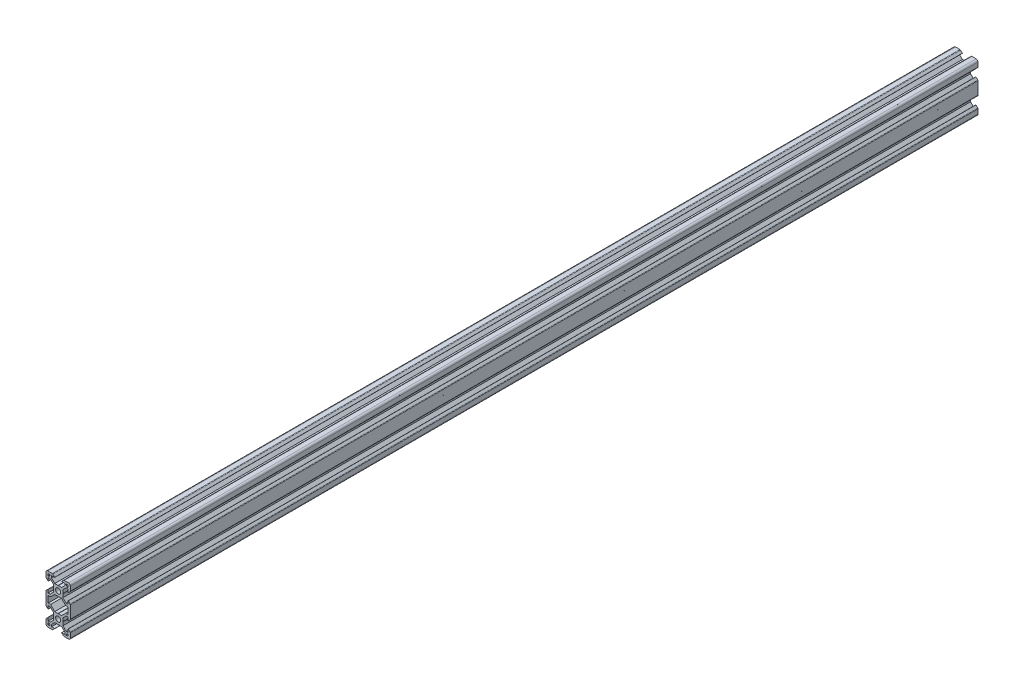
SolidWorks part; units mm, degrees
ref_plane "Front Plane" through (0, 0, 0) normal (0, 0, 1) x (1, 0, 0)
ref_plane "Top Plane" through (0, 0, 0) normal (0, 1, 0) x (1, 0, 0)
ref_plane "Right Plane" through (0, 0, 0) normal (1, 0, 0) x (0, 0, -1)
sketch "Sketch1" plane through (0, 0, 0) normal (0, 0, 1) x (1, 0, 0)
  line L0 (-8.2, 2.8875) -> (-8.2, 5.4975)
  line L3 (-4.9072, 9.9975) -> (-8.5, 9.9975)
  line L4 (-10, 4.9047) -> (-10, 8.4975)
  line L5 (-2.1, 0) -> (-3.8, 0) construction
  line L6 (0, 3.8) -> (0, 0) construction
  line L7 (-0.1, 3.9) -> (-2.8404, 3.9)
  line L8 (-3.9, 0.1) -> (-3.9, 2.8383)
  line L9 (-2.89, 8.1975) -> (-5.5, 8.1975)
  line L10 (-6.57, 8.1975) -> (-6.57, 7.6575)
  line L11 (-8.2, 6.5675) -> (-7.66, 6.5675)
  line L12 (-5.5, 8.1975) -> (-5.5, 6.5588)
  line L13 (-6.56, 5.4975) -> (-8.2, 5.4975)
  line L14 (-8.2, 8.1975) -> (-1.4852, 1.4847) construction
  line L15 (-6.56, 5.4975) -> (-3.9, 2.8383)
  line L16 (-5.5, 6.5588) -> (-2.8404, 3.9)
  line L17 (-7.66, 6.5675) -> (-6.57, 7.6575)
  line L18 (-8.7302, 7.6671) -> (-0.5302, -0.5304) construction
  line L19 (-7.6698, 8.7279) -> (0.5302, 0.5304) construction
  line L20 (-8.2, 8.1975) -> (0, 0) construction
  line L21 (-8.2, 6.5675) -> (-8.2, 8.1975)
  line L22 (-8.2, -0.0025) -> (-8.2, 8.1975) construction
  line L23 (-6.57, 8.1975) -> (-8.2, 8.1975)
  line L24 (0, 8.1975) -> (-8.2, 8.1975) construction
  line L25 (-10, -0.0025) -> (-10, 9.9975) construction
  line L26 (0, 9.9975) -> (-10, 9.9975) construction
  line L27 (-2.89, 8.3075) -> (-2.89, 8.1975)
  line L29 (-8.31, 2.8875) -> (-8.2, 2.8875)
  line L30 (-4.3486, 9.7661) -> (-2.89, 8.3075)
  line L31 (-8.31, 2.8875) -> (-9.7686, 4.3461)
  line L34 (-0.1, 3.9) -> (0, 3.8)
  line L35 (-3.9, 0.1) -> (-3.8, 0)
  line L36 (-8.2, -7.2996) -> (-6.24, -7.2996)
  line L37 (0, 0) -> (0, -10) construction
  line L38 (-0.1, -3.9) -> (-2.8404, -3.9)
  line L39 (-3.8, 0) -> (-3.9, -0.1)
  line L40 (-3.9, -0.1) -> (-3.9, -2.84)
  line L41 (-2.8404, -3.9) -> (-6.24, -7.2996)
  line L42 (-3.9, -2.84) -> (-6.56, -5.5)
  line L43 (-8.2, -2.89) -> (-8.2, -5.5)
  line L44 (-6.56, 5.4975) -> (-6.56, -5.5) construction
  line L45 (-6.56, -5.5) -> (-8.2, -5.5)
  line L46 (-0.1, -3.9) -> (0, -3.8)
  line L48 (-8.2, -2.89) -> (-8.31, -2.89)
  line L49 (-8.31, -2.89) -> (-9.7657, -4.3457)
  line L52 (-10, -10) -> (0, -10) construction
  line L53 (-8.2, -7.2996) -> (-8.2, -10)
  line L61 (-10, -4.9114) -> (-10, -10)
  arc A1 (-10, 8.4975) -> (-8.5, 9.9975) centre (-8.5, 8.4975) cw
  arc A2 (-9.7686, 4.3461) -> (-10, 4.9047) centre (-9.21, 4.9047) cw
  arc A3 (-4.3486, 9.7661) -> (-4.9072, 9.9975) centre (-4.9072, 9.2075) ccw
  arc A4 (-9.7657, -4.3457) -> (-10, -4.9114) centre (-9.2, -4.9114) ccw
  arc A6 (0, 2.1) -> (0, -2.1) centre (0, 0) ccw
  point P29 (-10, 9.9975)
  point P39 (-10, 4.5775)
  point P42 (-4.58, 9.9975)
  point P48 (-10, -4.58)
  dimension "D15" = 1.5
  dimension "D22" = 0.79
  dimension "D30" = 1.96
  dimension "D31" = 2.1
  dimension "D39" = 0.8
  dimension "D4" = 1.8
  dimension "D5" = 3.43
  dimension "D6" = 3.43
  dimension "D7" = 0.54
  dimension "D8" = 0.54
  dimension "D9" = 1.07
  dimension "D10" = 1.07
  dimension "D11" = 3.9
  dimension "D12" = 3.9
  dimension "D16" = 7.11
  dimension "D17" = 0.11
  dimension "D18" = 1.69
  dimension "D19" = 0.11
  dimension "D20" = 7.11
  dimension "D21" = 1.69
  dimension "D23" = 10
  dimension "D24" = 0.1
  dimension "D25" = 45
  dimension "D26" = 0.1
  dimension "D27" = 45
  dimension "D28" = 1.64
  dimension "D29" = 10
  dimension "D32" = 3.9
  dimension "D33" = 45
  dimension "D34" = 2.74
  dimension "D35" = 45
  dimension "D37" = 2.61
  dimension "D38" = 90
  dimension "D40" = 0.1
  dimension "D41" = 45
  dimension "D13" = 0.75
  dimension "D14" = 0.75
sketch "Sketch2" plane through (0, 0, 0) normal (0, 0, 1) x (1, 0, 0)
  line L0 (-0.1, 3.9) -> (0, 3.8) construction
  line L1 (-0.1, 3.9) -> (-2.8404, 3.9) construction
  line L2 (-5.5, 6.5588) -> (-2.8404, 3.9) construction
  line L3 (-5.5, 8.1975) -> (-5.5, 6.5588) construction
  line L4 (-2.89, 8.1975) -> (-5.5, 8.1975) construction
  line L5 (-7.66, 6.5675) -> (-6.57, 7.6575)
  line L6 (-6.57, 7.6575) -> (-6.57, 8.1975)
  line L7 (-6.57, 8.1975) -> (-8.2, 8.1975)
  line L8 (-8.2, 8.1975) -> (-8.2, 6.5675)
  line L9 (-8.2, 6.5675) -> (-7.66, 6.5675)
  line L10 (-7.66, 6.5675) -> (-6.57, 7.6575)
  line L11 (-6.57, 7.6575) -> (-6.57, 8.1975)
  line L12 (-6.57, 8.1975) -> (-8.2, 8.1975)
  line L13 (-8.2, 8.1975) -> (-8.2, 6.5675)
  line L14 (-8.2, 6.5675) -> (-7.66, 6.5675)
  line L15 (-2.89, 8.3075) -> (-2.89, 8.1975) construction
  line L16 (-4.3486, 9.7661) -> (-2.89, 8.3075) construction
  line L17 (-4.9072, 9.9975) -> (-8.5, 9.9975) construction
  line L18 (-10, 4.9047) -> (-10, 8.4975) construction
  line L19 (-8.31, 2.8875) -> (-9.7686, 4.3461) construction
  line L20 (-8.31, 2.8875) -> (-8.2, 2.8875) construction
  line L21 (-8.2, 2.8875) -> (-8.2, 5.4975) construction
  line L22 (-6.56, 5.4975) -> (-8.2, 5.4975) construction
  line L23 (-6.56, 5.4975) -> (-3.9, 2.8383) construction
  line L24 (-3.9, 0.1) -> (-3.9, 2.8383) construction
  line L25 (-3.9, 0.1) -> (-3.8, 0) construction
  line L26 (-3.8, 0) -> (-3.9, -0.1) construction
  line L27 (-3.9, -0.1) -> (-3.9, -2.84) construction
  line L28 (-3.9, -2.84) -> (-6.56, -5.5) construction
  line L29 (-6.56, -5.5) -> (-8.2, -5.5) construction
  line L30 (-8.2, -2.89) -> (-8.2, -5.5) construction
  line L31 (-8.2, -2.89) -> (-8.31, -2.89) construction
  line L32 (-8.31, -2.89) -> (-9.7657, -4.3457) construction
  line L33 (-10, -4.9114) -> (-10, -10) construction
  line L34 (-0.1, -3.9) -> (0, -3.8) construction
  line L35 (-0.1, -3.9) -> (-2.8404, -3.9) construction
  line L36 (-2.8404, -3.9) -> (-6.24, -7.2996) construction
  line L37 (-8.2, -7.2996) -> (-6.24, -7.2996) construction
  line L38 (-8.2, -7.2996) -> (-8.2, -10) construction
  line L39 (-0.1, 3.9) -> (0, 3.8)
  line L40 (-0.1, 3.9) -> (-2.8404, 3.9)
  line L41 (-5.5, 6.5588) -> (-2.8404, 3.9)
  line L42 (-5.5, 8.1975) -> (-5.5, 6.5588)
  line L43 (-2.89, 8.1975) -> (-5.5, 8.1975)
  line L44 (-2.89, 8.3075) -> (-2.89, 8.1975)
  line L45 (-4.3486, 9.7661) -> (-2.89, 8.3075)
  line L46 (-4.9072, 9.9975) -> (-8.5, 9.9975)
  line L47 (-10, 4.9047) -> (-10, 8.4975)
  line L48 (-8.31, 2.8875) -> (-9.7686, 4.3461)
  line L49 (-8.31, 2.8875) -> (-8.2, 2.8875)
  line L50 (-8.2, 2.8875) -> (-8.2, 5.4975)
  line L51 (-6.56, 5.4975) -> (-8.2, 5.4975)
  line L52 (-6.56, 5.4975) -> (-3.9, 2.8383)
  line L53 (-3.9, 0.1) -> (-3.9, 2.8383)
  line L54 (-3.9, 0.1) -> (-3.8, 0)
  line L55 (-3.8, 0) -> (-3.9, -0.1)
  line L56 (-3.9, -0.1) -> (-3.9, -2.84)
  line L57 (-3.9, -2.84) -> (-6.56, -5.5)
  line L58 (-6.56, -5.5) -> (-8.2, -5.5)
  line L59 (-8.2, -2.89) -> (-8.2, -5.5)
  line L60 (-8.2, -2.89) -> (-8.31, -2.89)
  line L61 (-8.31, -2.89) -> (-9.7657, -4.3457)
  line L62 (-10, -4.9114) -> (-10, -15.0886)
  line L63 (-0.1, -3.9) -> (0, -3.8)
  line L64 (-0.1, -3.9) -> (-2.8404, -3.9)
  line L65 (-2.8404, -3.9) -> (-6.24, -7.2996)
  line L66 (-8.2, -7.2996) -> (-6.24, -7.2996)
  line L67 (-8.2, -7.2996) -> (-8.2, -12.7004)
  line L68 (0, 0) -> (0, -10) construction
  line L69 (-10, -10) -> (0, -10) construction
  line L70 (0, 0) -> (0, -20) construction
  line L71 (-10, -10) -> (10, -10) construction
  line L72 (8.2, -7.2996) -> (8.2, -12.7004)
  line L73 (8.2, -7.2996) -> (6.24, -7.2996)
  line L74 (2.8404, -3.9) -> (6.24, -7.2996)
  line L75 (0.1, -3.9) -> (2.8404, -3.9)
  line L76 (0.1, -3.9) -> (0, -3.8)
  line L77 (10, -4.9114) -> (10, -15.0886)
  line L78 (8.31, -2.89) -> (9.7657, -4.3457)
  line L79 (8.2, -2.89) -> (8.31, -2.89)
  line L80 (8.2, -2.89) -> (8.2, -5.5)
  line L81 (6.56, -5.5) -> (8.2, -5.5)
  line L82 (3.9, -2.84) -> (6.56, -5.5)
  line L83 (3.9, -0.1) -> (3.9, -2.84)
  line L84 (3.8, 0) -> (3.9, -0.1)
  line L85 (3.9, 0.1) -> (3.8, 0)
  line L86 (3.9, 0.1) -> (3.9, 2.8383)
  line L87 (6.56, 5.4975) -> (3.9, 2.8383)
  line L88 (6.56, 5.4975) -> (8.2, 5.4975)
  line L89 (8.2, 2.8875) -> (8.2, 5.4975)
  line L90 (8.31, 2.8875) -> (8.2, 2.8875)
  line L91 (8.31, 2.8875) -> (9.7686, 4.3461)
  line L92 (10, 4.9047) -> (10, 8.4975)
  line L93 (4.9072, 9.9975) -> (8.5, 9.9975)
  line L94 (4.3486, 9.7661) -> (2.89, 8.3075)
  line L95 (2.89, 8.3075) -> (2.89, 8.1975)
  line L96 (2.89, 8.1975) -> (5.5, 8.1975)
  line L97 (5.5, 8.1975) -> (5.5, 6.5588)
  line L98 (5.5, 6.5588) -> (2.8404, 3.9)
  line L99 (0.1, 3.9) -> (2.8404, 3.9)
  line L100 (0.1, 3.9) -> (0, 3.8)
  line L101 (8.2, 6.5675) -> (7.66, 6.5675)
  line L102 (8.2, 8.1975) -> (8.2, 6.5675)
  line L103 (6.57, 8.1975) -> (8.2, 8.1975)
  line L104 (6.57, 7.6575) -> (6.57, 8.1975)
  line L105 (7.66, 6.5675) -> (6.57, 7.6575)
  line L106 (7.66, -26.5675) -> (6.57, -27.6575)
  line L107 (6.57, -27.6575) -> (6.57, -28.1975)
  line L108 (6.57, -28.1975) -> (8.2, -28.1975)
  line L109 (8.2, -28.1975) -> (8.2, -26.5675)
  line L110 (8.2, -26.5675) -> (7.66, -26.5675)
  line L111 (0.1, -23.9) -> (0, -23.8)
  line L112 (0.1, -23.9) -> (2.8404, -23.9)
  line L113 (5.5, -26.5588) -> (2.8404, -23.9)
  line L114 (5.5, -28.1975) -> (5.5, -26.5588)
  line L115 (2.89, -28.1975) -> (5.5, -28.1975)
  line L116 (2.89, -28.3075) -> (2.89, -28.1975)
  line L117 (4.3486, -29.7661) -> (2.89, -28.3075)
  line L118 (4.9072, -29.9975) -> (8.5, -29.9975)
  line L119 (10, -24.9047) -> (10, -28.4975)
  line L120 (8.31, -22.8875) -> (9.7686, -24.3461)
  line L121 (8.31, -22.8875) -> (8.2, -22.8875)
  line L122 (8.2, -22.8875) -> (8.2, -25.4975)
  line L123 (6.56, -25.4975) -> (8.2, -25.4975)
  line L124 (6.56, -25.4975) -> (3.9, -22.8383)
  line L125 (3.9, -20.1) -> (3.9, -22.8383)
  line L126 (3.9, -20.1) -> (3.8, -20)
  line L127 (3.8, -20) -> (3.9, -19.9)
  line L128 (3.9, -19.9) -> (3.9, -17.16)
  line L129 (3.9, -17.16) -> (6.56, -14.5)
  line L130 (6.56, -14.5) -> (8.2, -14.5)
  line L131 (8.2, -17.11) -> (8.2, -14.5)
  line L132 (8.2, -17.11) -> (8.31, -17.11)
  line L133 (8.31, -17.11) -> (9.7657, -15.6543)
  line L134 (0.1, -16.1) -> (0, -16.2)
  line L135 (0.1, -16.1) -> (2.8404, -16.1)
  line L136 (2.8404, -16.1) -> (6.24, -12.7004)
  line L137 (8.2, -12.7004) -> (6.24, -12.7004)
  line L138 (-8.2, -12.7004) -> (-6.24, -12.7004)
  line L139 (-2.8404, -16.1) -> (-6.24, -12.7004)
  line L140 (-0.1, -16.1) -> (-2.8404, -16.1)
  line L141 (-0.1, -16.1) -> (0, -16.2)
  line L142 (-8.31, -17.11) -> (-9.7657, -15.6543)
  line L143 (-8.2, -17.11) -> (-8.31, -17.11)
  line L144 (-8.2, -17.11) -> (-8.2, -14.5)
  line L145 (-6.56, -14.5) -> (-8.2, -14.5)
  line L146 (-3.9, -17.16) -> (-6.56, -14.5)
  line L147 (-3.9, -19.9) -> (-3.9, -17.16)
  line L148 (-3.8, -20) -> (-3.9, -19.9)
  line L149 (-3.9, -20.1) -> (-3.8, -20)
  line L150 (-3.9, -20.1) -> (-3.9, -22.8383)
  line L151 (-6.56, -25.4975) -> (-3.9, -22.8383)
  line L152 (-6.56, -25.4975) -> (-8.2, -25.4975)
  line L153 (-8.2, -22.8875) -> (-8.2, -25.4975)
  line L154 (-8.31, -22.8875) -> (-8.2, -22.8875)
  line L155 (-8.31, -22.8875) -> (-9.7686, -24.3461)
  line L156 (-10, -24.9047) -> (-10, -28.4975)
  line L157 (-4.9072, -29.9975) -> (-8.5, -29.9975)
  line L158 (-4.3486, -29.7661) -> (-2.89, -28.3075)
  line L159 (-2.89, -28.3075) -> (-2.89, -28.1975)
  line L160 (-2.89, -28.1975) -> (-5.5, -28.1975)
  line L161 (-5.5, -28.1975) -> (-5.5, -26.5588)
  line L162 (-5.5, -26.5588) -> (-2.8404, -23.9)
  line L163 (-0.1, -23.9) -> (-2.8404, -23.9)
  line L164 (-0.1, -23.9) -> (0, -23.8)
  line L165 (-8.2, -26.5675) -> (-7.66, -26.5675)
  line L166 (-8.2, -28.1975) -> (-8.2, -26.5675)
  line L167 (-6.57, -28.1975) -> (-8.2, -28.1975)
  line L168 (-6.57, -27.6575) -> (-6.57, -28.1975)
  line L169 (-7.66, -26.5675) -> (-6.57, -27.6575)
  arc A0 (0, 2.1) -> (0, -2.1) centre (0, 0) ccw construction
  arc A1 (-4.3486, 9.7661) -> (-4.9072, 9.9975) centre (-4.9072, 9.2075) ccw construction
  arc A2 (-8.5, 9.9975) -> (-10, 8.4975) centre (-8.5, 8.4975) ccw construction
  arc A3 (-10, 4.9047) -> (-9.7686, 4.3461) centre (-9.21, 4.9047) ccw construction
  arc A4 (-9.7657, -4.3457) -> (-10, -4.9114) centre (-9.2, -4.9114) ccw construction
  circle A5 centre (0, 0) radius 2.1
  arc A6 (-4.3486, 9.7661) -> (-4.9072, 9.9975) centre (-4.9072, 9.2075) ccw
  arc A7 (-8.5, 9.9975) -> (-10, 8.4975) centre (-8.5, 8.4975) ccw
  arc A8 (-10, 4.9047) -> (-9.7686, 4.3461) centre (-9.21, 4.9047) ccw
  arc A9 (-9.7657, -4.3457) -> (-10, -4.9114) centre (-9.2, -4.9114) ccw
  arc A10 (9.7657, -4.3457) -> (10, -4.9114) centre (9.2, -4.9114) cw
  arc A11 (10, 4.9047) -> (9.7686, 4.3461) centre (9.21, 4.9047) cw
  arc A12 (8.5, 9.9975) -> (10, 8.4975) centre (8.5, 8.4975) cw
  arc A13 (4.3486, 9.7661) -> (4.9072, 9.9975) centre (4.9072, 9.2075) cw
  arc A14 (4.3486, -29.7661) -> (4.9072, -29.9975) centre (4.9072, -29.2075) ccw
  arc A15 (8.5, -29.9975) -> (10, -28.4975) centre (8.5, -28.4975) ccw
  arc A16 (10, -24.9047) -> (9.7686, -24.3461) centre (9.21, -24.9047) ccw
  arc A17 (9.7657, -15.6543) -> (10, -15.0886) centre (9.2, -15.0886) ccw
  arc A18 (-9.7657, -15.6543) -> (-10, -15.0886) centre (-9.2, -15.0886) cw
  arc A19 (-10, -24.9047) -> (-9.7686, -24.3461) centre (-9.21, -24.9047) cw
  arc A20 (-8.5, -29.9975) -> (-10, -28.4975) centre (-8.5, -28.4975) cw
  arc A21 (-4.3486, -29.7661) -> (-4.9072, -29.9975) centre (-4.9072, -29.2075) cw
  circle A22 centre (0, -20) radius 2.1
  point P147 (8.2, -10)
  dimension "D1" = 0
extrude "Boss-Extrude1" add sketch "Sketch2" against normal up to surface (746 mm away)
